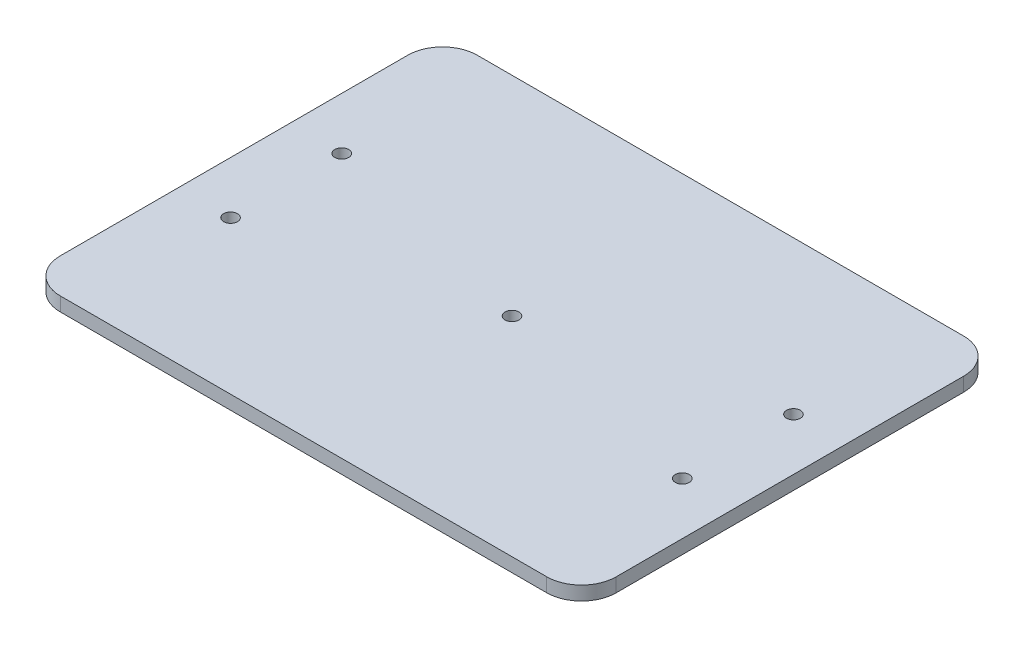
SolidWorks part; units mm, degrees
ref_plane "Front Plane" through (0, 0, 0) normal (0, 0, 1) x (1, 0, 0)
ref_plane "Top Plane" through (0, 0, 0) normal (0, 1, 0) x (1, 0, 0)
ref_plane "Right Plane" through (0, 0, 0) normal (1, 0, 0) x (0, 0, -1)
sketch "Sketch1" plane through (0, 0, 0) normal (0, 1, 0) x (1, 0, 0)
  line L1 (-39.5316, 20.9836) -> (40.4684, 20.9836)
  line L2 (-39.5316, 20.9836) -> (-39.5316, -39.0164)
  line L3 (-39.5316, -39.0164) -> (40.4684, -39.0164)
  line L4 (40.4684, 20.9836) -> (40.4684, -39.0164)
  dimension "D1" = 80
  dimension "D2" = 60
extrude "Boss-Extrude2" add sketch "Sketch1" along normal blind 2
sketch "Sketch3" plane through (0, 2, 0) normal (0, 1, 0) x (1, 0, 0)
  line L0 (40.4684, 20.9836) -> (-39.5316, 20.9836) construction
  line L1 (-39.5316, -39.0164) -> (40.4684, -39.0164) construction
  line L2 (-39.5316, 20.9836) -> (-39.5316, -39.0164) construction
  line L3 (40.4684, -39.0164) -> (40.4684, 20.9836) construction
  circle A0 centre (-32.0316, -1.0164) radius 1
  circle A1 centre (-32.0316, -17.0164) radius 1
  circle A2 centre (32.9684, -1.0164) radius 1
  circle A3 centre (32.9684, -17.0164) radius 1
  circle A4 centre (0.4684, -9.0164) radius 1
  dimension "D1" = 22
  dimension "D5" = 22
  dimension "D9" = 30
  dimension "D2" = 22
  dimension "D3" = 7.5
  dimension "D4" = 7.5
  dimension "D6" = 7.5
  dimension "D7" = 7.5
  dimension "D8" = 22
  dimension "D10" = 40
extrude "Cut-Extrude2" cut sketch "Sketch3" against normal blind 2
fillet "Fillet2" radius 5 4 edges at (40.4684, 1, -20.9836) (40.4684, 1, 39.0164) (-39.5316, 1, 39.0164) (-39.5316, 1, -20.9836)
